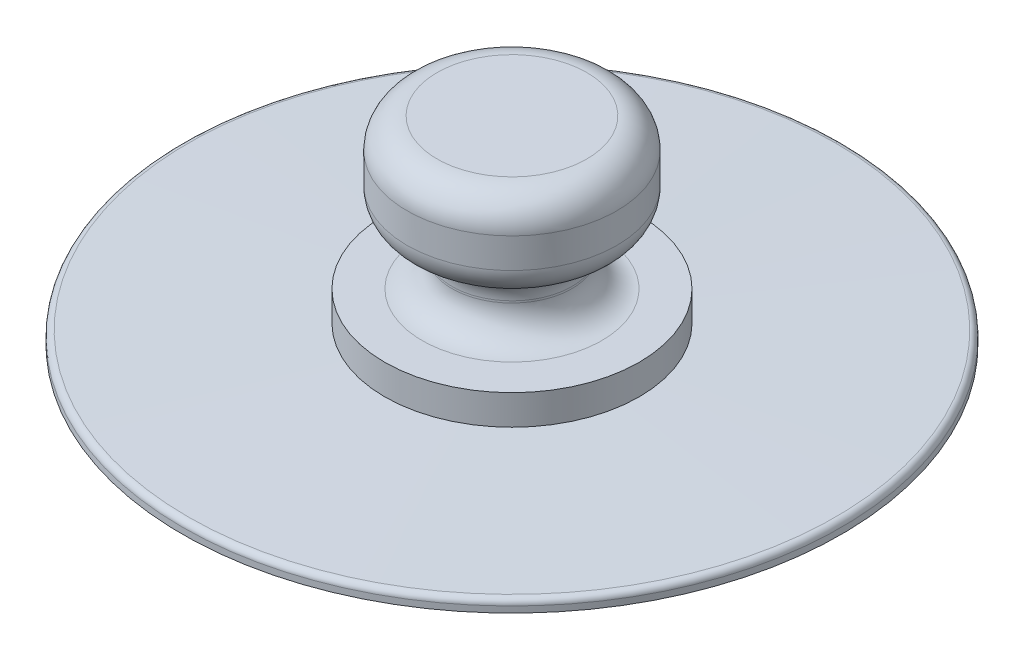
SolidWorks part; units mm, degrees
ref_plane "Front Plane" through (0, 0, 0) normal (0, 0, 1) x (1, 0, 0)
ref_plane "Top Plane" through (0, 0, 0) normal (0, 1, 0) x (1, 0, 0)
ref_plane "Right Plane" through (0, 0, 0) normal (1, 0, 0) x (0, 0, -1)
sketch "Sketch1" plane through (0, 0, 0) normal (1, 0, 0) x (0, 0, -1)
  line L0 (0, 0) -> (0, 50000) construction
  line L1 (0, 0) -> (50000, 0) construction
  line L2 (-11, 0) -> (-10, 0)
  line L3 (-10, 0) -> (0, 0.1)
  line L4 (0, 0.1) -> (0, 6.6)
  line L5 (0, 6.6) -> (-3.5, 6.6)
  line L6 (-3.5, 6.6) -> (-3.5, 3.6)
  line L7 (-3.5, 3.6) -> (-2, 3.6)
  line L8 (-2, 3.6) -> (-2, 1.6)
  line L9 (-2, 1.6) -> (-4.25, 1.6)
  line L10 (-4.25, 1.6) -> (-4.25, 0.6)
  line L11 (-11, 0) -> (-11, 0.4)
  line L12 (-11, 0.4) -> (-4.25, 0.6)
  dimension "D1" = 1
  dimension "D2" = 2
  dimension "D3" = 3
  dimension "D4" = 7
  dimension "D5" = 4
  dimension "D6" = 8.5
  dimension "D7" = 1.6
  dimension "D8" = 20
  dimension "D9" = 22
  dimension "D10" = 1.5
  dimension "D11" = 0.4
revolve "Revolve1" add sketch "Sketch1" angle 360 about L0
fillet "Fillet1" radius 1 2 edges at (0, 3.6, -3.5) (0, 6.6, -3.5)
fillet "Fillet2" radius 1 2 edges at (0, 1.6, -2) (0, 3.6, -2)
fillet "Fillet3" radius 0.2 1 edges at (0, 0.4, -11)
